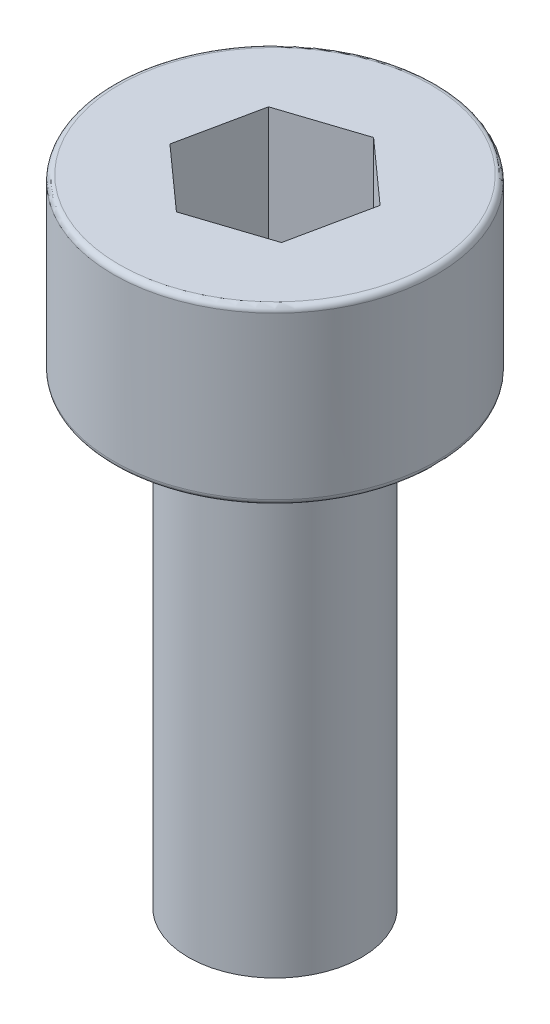
SolidWorks part; units mm, degrees
ref_plane "前视基准面" through (0, 0, 0) normal (0, 0, 1) x (1, 0, 0)
ref_plane "上视基准面" through (0, 0, 0) normal (0, 1, 0) x (1, 0, 0)
ref_plane "右视基准面" through (0, 0, 0) normal (1, 0, 0) x (0, 0, -1)
sketch "草图1" plane through (0, 0, 0) normal (0, 0, 1) x (1, 0, 0)
  line L0 (0, 0) -> (0, 11)
  line L1 (0, 11) -> (2.8, 11)
  line L2 (2.8, 11) -> (2.8, 8)
  line L3 (2.8, 8) -> (1.5, 8)
  line L4 (1.5, 8) -> (1.5, 0)
  line L5 (1.5, 0) -> (0, 0)
  dimension "D1" = 3
  dimension "D2" = 8
  dimension "D3" = 2.8
  dimension "D4" = 1.5
revolve "旋转1" add sketch "草图1" angle 360 about L0
cosmetic thread "装饰螺纹线1" parameters "D2"=2
sketch "草图2" plane through (0, 11, 0) normal (0, 1, 0) x (1, 0, 0)
  line L1 (1.0753, -0.9628) -> (1.3715, 0.4498)
  line L2 (1.3715, 0.4498) -> (0.2962, 1.4127)
  line L3 (0.2962, 1.4127) -> (-1.0753, 0.9628)
  line L4 (-1.0753, 0.9628) -> (-1.3715, -0.4498)
  line L5 (-1.3715, -0.4498) -> (-0.2962, -1.4127)
  line L6 (-0.2962, -1.4127) -> (1.0753, -0.9628)
  circle A0 centre (0, 0) radius 1.25 construction
  dimension "D1" = 2.5
extrude "切除-拉伸1" cut sketch "草图2" against normal blind 2
fillet "圆角1" radius 0.1 2 edges at (0, 8, -2.8) (0, 11, -2.8)
